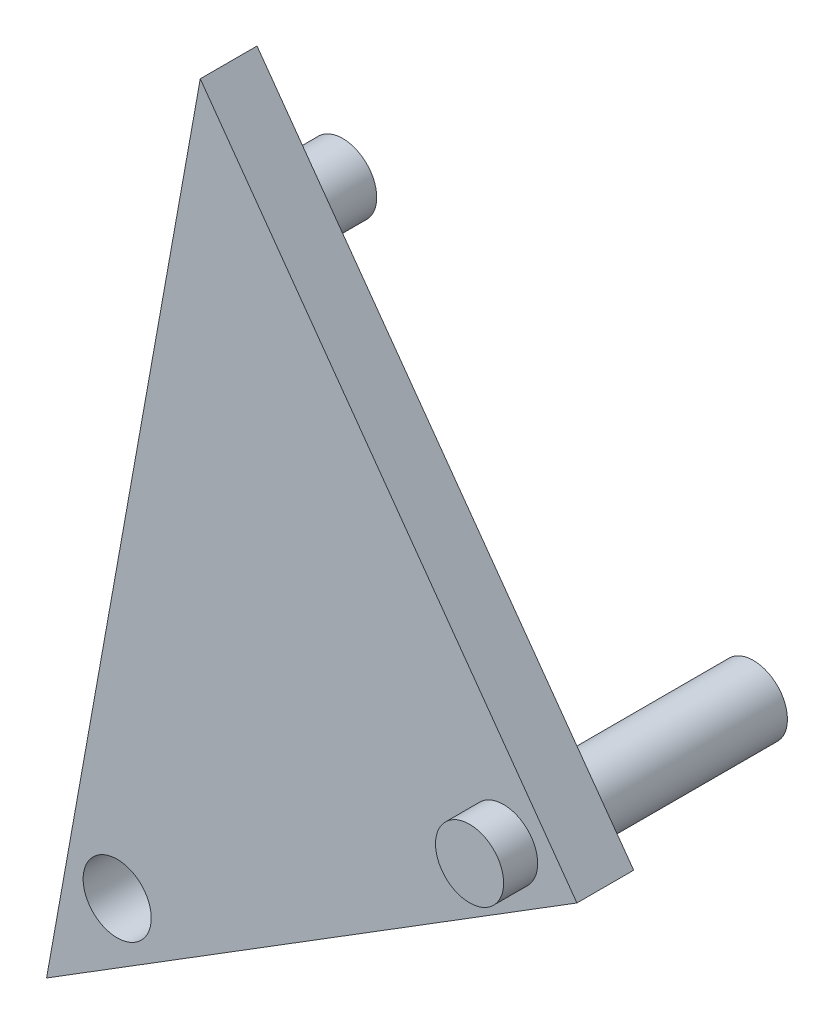
SolidWorks part; units mm, degrees
ref_plane "Front Plane" through (0, 0, 0) normal (0, 0, 1) x (1, 0, 0)
ref_plane "Top Plane" through (0, 0, 0) normal (0, 1, 0) x (1, 0, 0)
ref_plane "Right Plane" through (0, 0, 0) normal (1, 0, 0) x (0, 0, -1)
sketch "Sketch1" plane through (0, 0, 0) normal (0, 0, 1) x (1, 0, 0)
  line L9 (-26.7245, 45.0059) -> (-40.2626, -30.3639)
  line L10 (-40.2626, -30.3639) -> (6.4557, -1.282)
  line L11 (6.4557, -1.282) -> (-26.7245, 45.0059)
  circle A0 centre (-24.178, 33.7294) radius 3
  circle A1 centre (0, 0) radius 3
  circle A2 centre (-34.043, -21.1916) radius 3
  dimension "D5" = 6
  dimension "D6" = 6
  dimension "D7" = 6
  dimension "D1" = 41.5
  dimension "D2" = 55.8
  dimension "D3" = 40.1
extrude "Boss-Extrude1" add sketch "Sketch1" along normal blind 5
sketch "Sketch2" plane through (0, 0, 5) normal (0, 0, 1) x (1, 0, 0)
  circle A0 centre (-24.178, 33.7294) radius 3
extrude "Boss-Extrude2" add sketch "Sketch2" against normal blind 10
sketch "Sketch3" plane through (0, 0, 5) normal (0, 0, 1) x (1, 0, 0)
  circle A0 centre (0, 0) radius 3
extrude "Boss-Extrude3" add sketch "Sketch3" against normal blind 22
sketch "Sketch4" plane through (0, 0, 5) normal (0, 0, 1) x (1, 0, 0)
  circle A0 centre (0, 0) radius 3
  dimension "D1" = 6
extrude "Boss-Extrude4" add sketch "Sketch4" along normal blind 3
